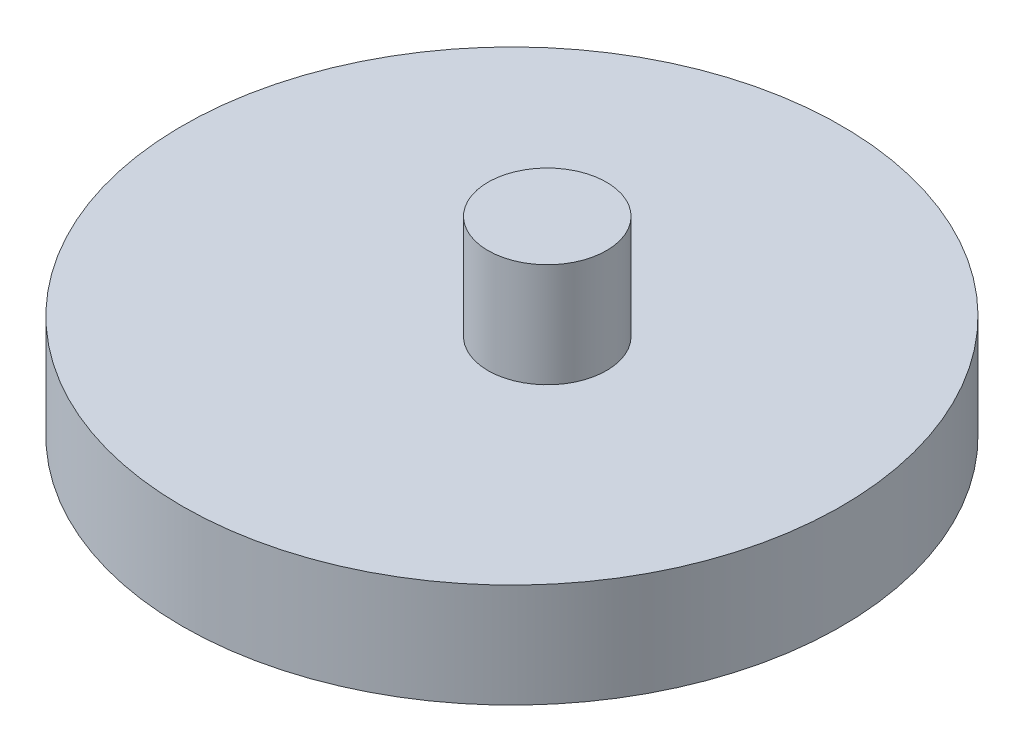
SolidWorks part; units mm, degrees
ref_plane "Front Plane" through (0, 0, 0) normal (0, 0, 1) x (1, 0, 0)
ref_plane "Top Plane" through (0, 0, 0) normal (0, 1, 0) x (1, 0, 0)
ref_plane "Right Plane" through (0, 0, 0) normal (1, 0, 0) x (0, 0, -1)
sketch "Sketch1" plane through (0, 0, 0) normal (0, 1, 0) x (1, 0, 0)
  circle A0 centre (0, 0) radius 20.1295
  dimension "D1" = 40.259
extrude "Boss-Extrude1" add sketch "Sketch1" along normal blind 6.35
sketch "Sketch2" plane through (0, 6.35, 0) normal (0, 1, 0) x (1, 0, 0)
  line L0 (0, 0) -> (2.159, 0) construction
  circle A0 centre (2.159, 0) radius 3.6195
  dimension "D1" = 7.239
  dimension "D2" = 2.159
extrude "Boss-Extrude2" add sketch "Sketch2" along normal blind 6.35
